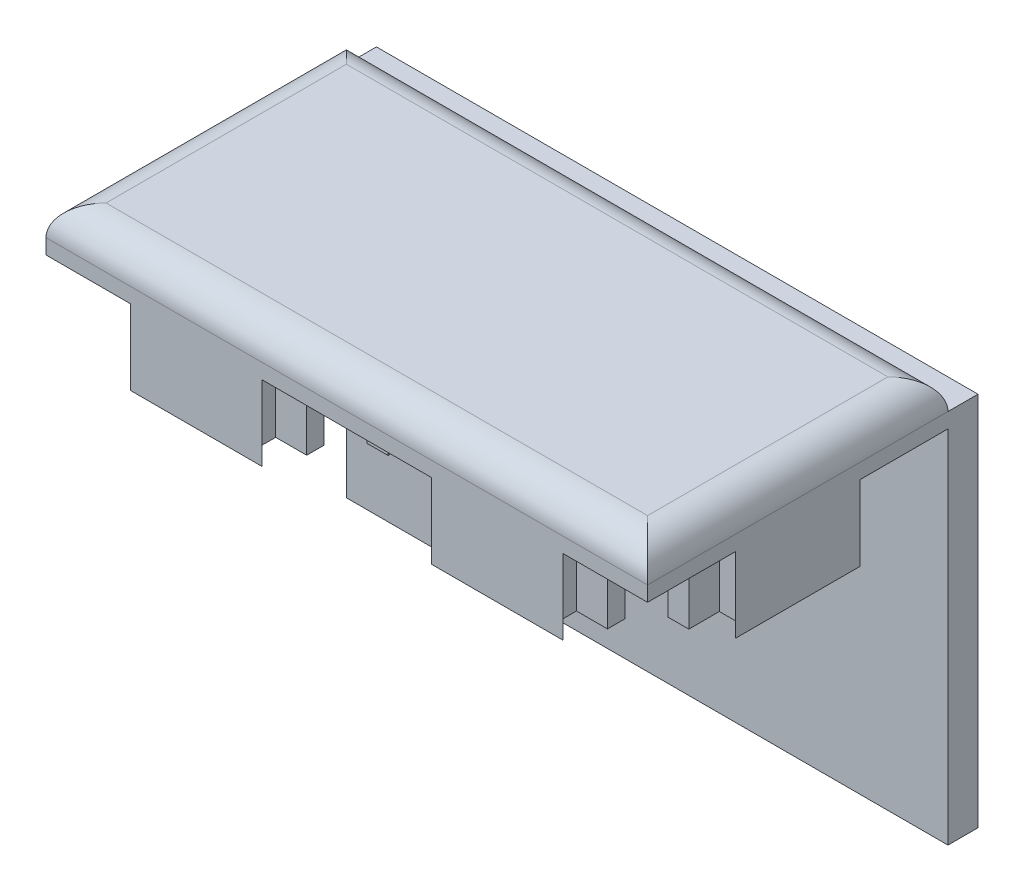
SolidWorks part; units mm, degrees
ref_plane "Alzado" through (0, 0, 0) normal (0, 0, 1) x (1, 0, 0)
ref_plane "Planta" through (0, 0, 0) normal (0, 1, 0) x (1, 0, 0)
ref_plane "Vista lateral" through (0, 0, 0) normal (1, 0, 0) x (0, 0, -1)
sketch "Croquis1" plane through (0, 0, 0) normal (0, 1, 0) x (1, 0, 0)
  line L0 (0, 10) -> (0, -10) construction
  line L1 (-20, -10) -> (20, -10) construction
  line L2 (-20, -10) -> (-20, 10) construction
  line L3 (-20, 10) -> (20, 10) construction
  line L4 (20, -10) -> (20, 10) construction
  line L5 (-20, -10) -> (20, 10) construction
  line L6 (-20, 10) -> (20, -10) construction
  point P0 (0, 0)
  dimension "D1" = 40
  dimension "D2" = 20
sketch "Croquis2" plane through (0, 0, 0) normal (0, 1, 0) x (1, 0, 0)
  line L0 (9.987, 12.4017) -> (9.987, -10.9745) construction
  line L1 (5.615, 10) -> (14.359, 10)
  line L2 (-0.026, 14.7538) -> (-0.026, 4.155) construction
  line L3 (-20, 10) -> (20, 10) construction
  line L4 (4.7752, 6.7111) -> (7.2921, 4.1942)
  line L5 (4.7752, 7.8686) -> (4.7752, 6.7111)
  line L6 (6.8395, 7.8686) -> (4.7752, 7.8686)
  line L7 (6.8395, 8.7755) -> (6.8395, 7.8686)
  line L8 (14.359, 10) -> (13.1345, 8.7755)
  line L9 (13.1345, 8.7755) -> (13.1345, 7.8686)
  line L10 (13.1345, 7.8686) -> (15.1988, 7.8686)
  line L11 (15.1988, 7.8686) -> (15.1988, 6.7111)
  line L12 (15.1988, 6.7111) -> (12.6819, 4.1942)
  line L13 (12.6819, 4.1942) -> (7.2921, 4.1942)
  line L14 (5.615, 10) -> (6.8395, 8.7755)
  line L15 (0, 0) -> (25.8416, 0) construction
  line L16 (20, 4.155) -> (20, -4.155)
  line L17 (-0.026, 4.155) -> (-1.0402, 3.1408)
  line L18 (20, -10) -> (20, 10) construction
  line L19 (20, -4.155) -> (18.9858, -3.1408)
  line L20 (18.9858, -3.1408) -> (17.9195, -3.1408)
  line L21 (17.9195, -3.1408) -> (17.9195, -5.173)
  line L22 (17.9195, -5.173) -> (16.5315, -5.173)
  line L23 (20, 4.155) -> (18.9858, 3.1408)
  line L24 (18.9858, 3.1408) -> (17.9195, 3.1408)
  line L25 (17.9195, 3.1408) -> (17.9195, 5.173)
  line L26 (17.9195, 5.173) -> (16.5315, 5.173)
  line L27 (16.5315, 5.173) -> (14.1751, 2.8166)
  line L28 (14.1751, 2.8166) -> (14.1751, -2.8166)
  line L29 (16.5315, -5.173) -> (14.1751, -2.8166)
  line L30 (4.7752, -6.7111) -> (7.2921, -4.1942)
  line L31 (4.7752, -7.8686) -> (4.7752, -6.7111)
  line L32 (6.8395, -7.8686) -> (4.7752, -7.8686)
  line L33 (6.8395, -8.7755) -> (6.8395, -7.8686)
  line L34 (5.615, -10) -> (6.8395, -8.7755)
  line L35 (5.615, -10) -> (14.359, -10)
  line L36 (14.359, -10) -> (13.1345, -8.7755)
  line L37 (13.1345, -8.7755) -> (13.1345, -7.8686)
  line L38 (13.1345, -7.8686) -> (15.1988, -7.8686)
  line L39 (15.1988, -7.8686) -> (15.1988, -6.7111)
  line L40 (15.1988, -6.7111) -> (12.6819, -4.1942)
  line L41 (12.6819, -4.1942) -> (7.2921, -4.1942)
  line L42 (3.4425, 5.173) -> (5.7989, 2.8166)
  line L43 (5.7989, 2.8166) -> (5.7989, -2.8166)
  line L44 (3.4425, -5.173) -> (5.7989, -2.8166)
  line L45 (2.0545, -5.173) -> (3.4425, -5.173)
  line L46 (2.0545, -3.1408) -> (2.0545, -5.173)
  line L47 (0.9882, -3.1408) -> (2.0545, -3.1408)
  line L48 (-0.026, -4.155) -> (0.9882, -3.1408)
  line L50 (-0.026, 4.155) -> (0.9882, 3.1408)
  line L51 (0.9882, 3.1408) -> (2.0545, 3.1408)
  line L52 (2.0545, 3.1408) -> (2.0545, 5.173)
  line L53 (2.0545, 5.173) -> (3.4425, 5.173)
  line L54 (-0.026, -4.155) -> (-1.0402, -3.1408)
  line L55 (-1.0402, -3.1408) -> (-2.1065, -3.1408)
  line L56 (-1.0402, 3.1408) -> (-2.1065, 3.1408)
  line L57 (-10.039, 12.4017) -> (-10.039, -10.9745) construction
  line L58 (-2.1065, 5.173) -> (-3.4945, 5.173)
  line L59 (-2.1065, 3.1408) -> (-2.1065, 5.173)
  line L60 (-2.1065, -3.1408) -> (-2.1065, -5.173)
  line L61 (-2.1065, -5.173) -> (-3.4945, -5.173)
  line L62 (-3.4945, -5.173) -> (-5.8509, -2.8166)
  line L63 (-5.8509, 2.8166) -> (-5.8509, -2.8166)
  line L64 (-3.4945, 5.173) -> (-5.8509, 2.8166)
  line L65 (-12.7339, -4.1942) -> (-7.3442, -4.1942)
  line L66 (-15.2508, -6.7111) -> (-12.7339, -4.1942)
  line L67 (-15.2508, -7.8686) -> (-15.2508, -6.7111)
  line L68 (-13.1865, -7.8686) -> (-15.2508, -7.8686)
  line L69 (-13.1865, -8.7755) -> (-13.1865, -7.8686)
  line L70 (-14.411, -10) -> (-13.1865, -8.7755)
  line L71 (-5.667, -10) -> (-14.411, -10)
  line L72 (-5.667, -10) -> (-6.8915, -8.7755)
  line L73 (-6.8915, -8.7755) -> (-6.8915, -7.8686)
  line L74 (-6.8915, -7.8686) -> (-4.8272, -7.8686)
  line L75 (-4.8272, -7.8686) -> (-4.8272, -6.7111)
  line L76 (-4.8272, -6.7111) -> (-7.3442, -4.1942)
  line L77 (-16.5836, -5.173) -> (-14.2271, -2.8166)
  line L78 (-14.2271, 2.8166) -> (-14.2271, -2.8166)
  line L79 (-16.5836, 5.173) -> (-14.2271, 2.8166)
  line L80 (-17.9715, 5.173) -> (-16.5836, 5.173)
  line L81 (-17.9715, 3.1408) -> (-17.9715, 5.173)
  line L82 (-19.0378, 3.1408) -> (-17.9715, 3.1408)
  line L83 (-20.052, 4.155) -> (-19.0378, 3.1408)
  line L84 (-17.9715, -5.173) -> (-16.5836, -5.173)
  line L85 (-17.9715, -3.1408) -> (-17.9715, -5.173)
  line L86 (-19.0378, -3.1408) -> (-17.9715, -3.1408)
  line L87 (-20.052, -4.155) -> (-19.0378, -3.1408)
  line L88 (-20.052, 4.155) -> (-20.052, -4.155)
  line L89 (-5.667, 10) -> (-6.8915, 8.7755)
  line L90 (-12.7339, 4.1942) -> (-7.3442, 4.1942)
  line L91 (-15.2508, 6.7111) -> (-12.7339, 4.1942)
  line L92 (-15.2508, 7.8686) -> (-15.2508, 6.7111)
  line L93 (-13.1865, 7.8686) -> (-15.2508, 7.8686)
  line L94 (-13.1865, 8.7755) -> (-13.1865, 7.8686)
  line L95 (-14.411, 10) -> (-13.1865, 8.7755)
  line L96 (-6.8915, 8.7755) -> (-6.8915, 7.8686)
  line L97 (-6.8915, 7.8686) -> (-4.8272, 7.8686)
  line L98 (-4.8272, 7.8686) -> (-4.8272, 6.7111)
  line L99 (-4.8272, 6.7111) -> (-7.3442, 4.1942)
  line L100 (-5.667, 10) -> (-14.411, 10)
  line L101 (-0.026, -4.155) -> (-0.026, -16.1142) construction
  circle A0 centre (-10.039, 0) radius 1.7797
  circle A1 centre (9.987, 0) radius 1.7797
  point P7 (9.987, 4.1942)
  point P18 (9.987, 10)
  point P26 (20, 0)
  point P37 (14.1751, 0)
  point P111 (-14.2271, 0)
  point P112 (-20.052, 0)
  point P113 (-10.039, 10)
  point P114 (-10.039, 4.1942)
extrude "Saliente-Extruir1" add sketch "Croquis2" along normal blind 5
sketch "Croquis3" plane through (0, 5, 0) normal (0, 1, 0) x (1, 0, 0)
  line L0 (-10.039, -10) -> (9.987, -10) construction
  line L1 (-10.039, 10) -> (9.987, 10) construction
  line L2 (-5.667, 10) -> (-14.411, 10) construction
  line L3 (14.359, 10) -> (5.615, 10) construction
  line L4 (-14.411, -10) -> (-5.667, -10) construction
  line L5 (5.615, -10) -> (14.359, -10) construction
  line L6 (-20.052, 0) -> (20, 0) construction
  line L7 (-20.052, 4.155) -> (-20.052, -4.155) construction
  line L8 (20, -4.155) -> (20, 4.155) construction
  line L10 (-20.052, 10) -> (20, 10)
  line L11 (-20.052, 10) -> (-20.052, -10)
  line L12 (-20.052, -10) -> (20, -10)
  line L13 (20, 10) -> (20, -10)
extrude "Saliente-Extruir2" add sketch "Croquis3" along normal blind 3
fillet "Redondeo1" radius 2 4 edges at (-20.052, 8, 0) (-0.026, 8, 10) (20, 8, 0) (-0.026, 8, -10)
sketch "Croquis4" plane through (0, 0, -10) normal (0, 0, -1) x (-1, 0, 0)
  line L1 (-20, 6) -> (20.052, 6)
  line L2 (-20, 6) -> (-20, -19)
  line L3 (-20, -19) -> (20.052, -19)
  line L4 (20.052, 6) -> (20.052, -19)
  dimension "D1" = 25
extrude "Saliente-Extruir3" add sketch "Croquis4" along normal blind 3
chamfer "Chaflán1" distance 1 angle 45 4 edges at (20, -6.5, -13) (-0.026, -19, -13) (-20.052, -6.5, -13) (-0.026, 6, -13)
